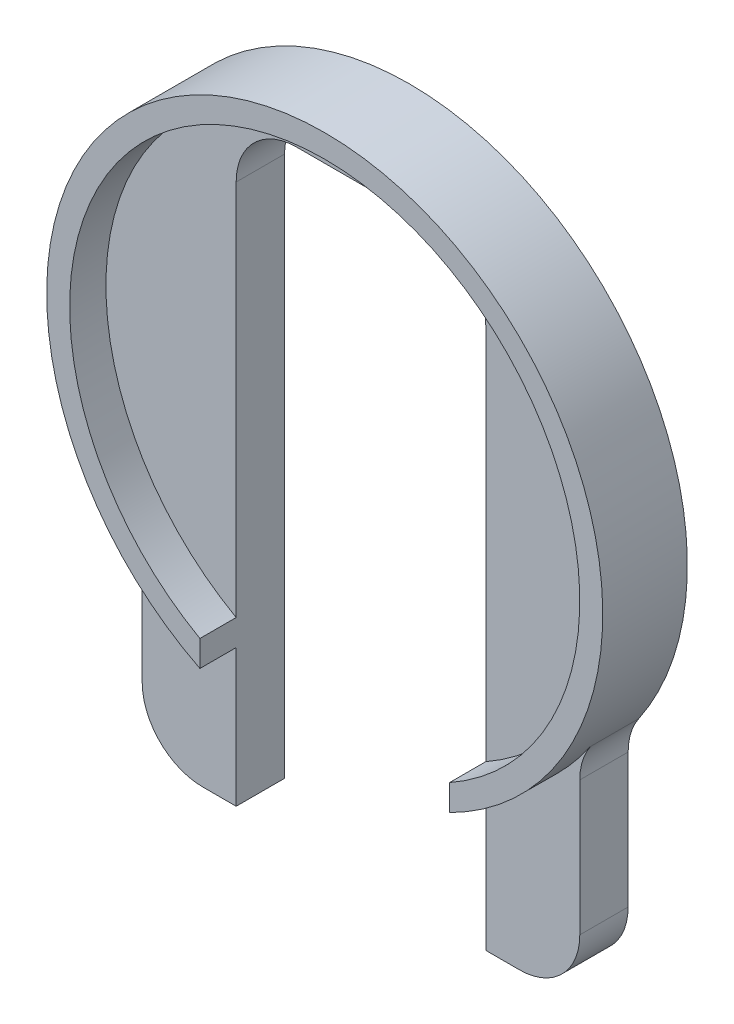
SolidWorks part; units mm, degrees
material "ABS"
ref_plane "Front Plane" through (0, 0, 0) normal (0, 0, 1) x (1, 0, 0)
ref_plane "Top Plane" through (0, 0, 0) normal (0, 1, 0) x (1, 0, 0)
ref_plane "Right Plane" through (0, 0, 0) normal (1, 0, 0) x (0, 0, -1)
sketch "Sketch1" plane through (0, 0, 0) normal (0, 0, 1) x (1, 0, 0)
  line L0 (0, 10.325) -> (0, -31.925) construction
  line L1 (-10.325, 10.325) -> (10.325, 10.325) construction
  line L2 (-10.325, 10.325) -> (-10.325, -31.925)
  line L3 (-10.325, -31.925) -> (10.325, -31.925) construction
  line L4 (10.325, 10.325) -> (10.325, -31.925)
  line L5 (-10.325, -10.8) -> (10.325, -10.8) construction
  line L6 (10.325, 10.325) -> (10.325, 17.8)
  line L7 (-10.325, 10.325) -> (-10.325, 17.8)
  line L8 (-10.325, 17.8) -> (10.325, 17.8)
  line L9 (-10.325, -31.925) -> (-18.1, -31.925)
  line L10 (-18.1, -31.925) -> (-18.1, -14.1912)
  line L11 (10.325, -31.925) -> (18.1, -31.925)
  line L12 (18.1, -31.925) -> (18.1, -14.1912)
  circle A0 centre (0, 0) radius 6.5 construction
  circle A1 centre (-4.9, 14.8) radius 1.5 construction
  circle A2 centre (4.9, 14.8) radius 1.5 construction
  circle A3 centre (-4.9, -36.4) radius 1.5 construction
  circle A4 centre (4.9, -36.4) radius 1.5 construction
  circle A5 centre (-4.9, 14.8) radius 3 construction
  circle A6 centre (4.9, 14.8) radius 3 construction
  circle A7 centre (4.9, -36.4) radius 3 construction
  circle A8 centre (-4.9, -36.4) radius 3 construction
  circle A9 centre (0, 0) radius 21 construction
  arc A10 (18.1, -14.1912) -> (-18.1, -14.1912) centre (0, 0) ccw
  dimension "D1" = 13
  dimension "D5" = 3
  dimension "D8" = 6
  dimension "D9" = 42
  dimension "D10" = 2
  dimension "D2" = 42.25
  dimension "D3" = 20.65
  dimension "D4" = 10.8
  dimension "D6" = 9.8
  dimension "D7" = 25.6
  dimension "D11" = 36.2
extrude "Boss-Extrude1" add sketch "Sketch1" along normal blind 4
sketch "Sketch2" plane through (0, 0, 4) normal (0, 0, 1) x (1, 0, 0)
  line L1 (-10.325, -18.4012) -> (-10.325, -20.5522)
  line L3 (10.325, -18.4012) -> (10.325, -20.5522)
  line L5 (-10.325, -31.925) -> (-10.325, 17.8) construction
  line L6 (10.325, 17.8) -> (10.325, -31.925) construction
  arc A0 (10.325, -18.4012) -> (-10.325, -18.4012) centre (0, 0) ccw
  arc A2 (18.1, -14.1912) -> (-18.1, -14.1912) centre (0, 0) ccw construction
  arc A3 (10.325, -20.5522) -> (-10.325, -20.5522) centre (0, 0) ccw
  dimension "D1" = 42.2
extrude "Boss-Extrude2" add sketch "Sketch2" along normal blind 3
fillet "Fillet1" radius 5 2 edges at (10.325, 17.8, 2) (-10.325, 17.8, 2)
fillet "Fillet2" radius 5 4 edges at (18.1, -31.925, 2) (-18.1, -31.925, 2)
equation "\"D1@Sketch2\"=42.00mm+\"print_fit@Parameters@Parameters.SLDPRT\""
equation "\"D3@Sketch1\"=20.20mm+\"print_free@Parameters@Parameters.SLDPRT\""
equation "\"D2@Sketch1\"=41.80mm+\"print_free@Parameters@Parameters.SLDPRT\""
